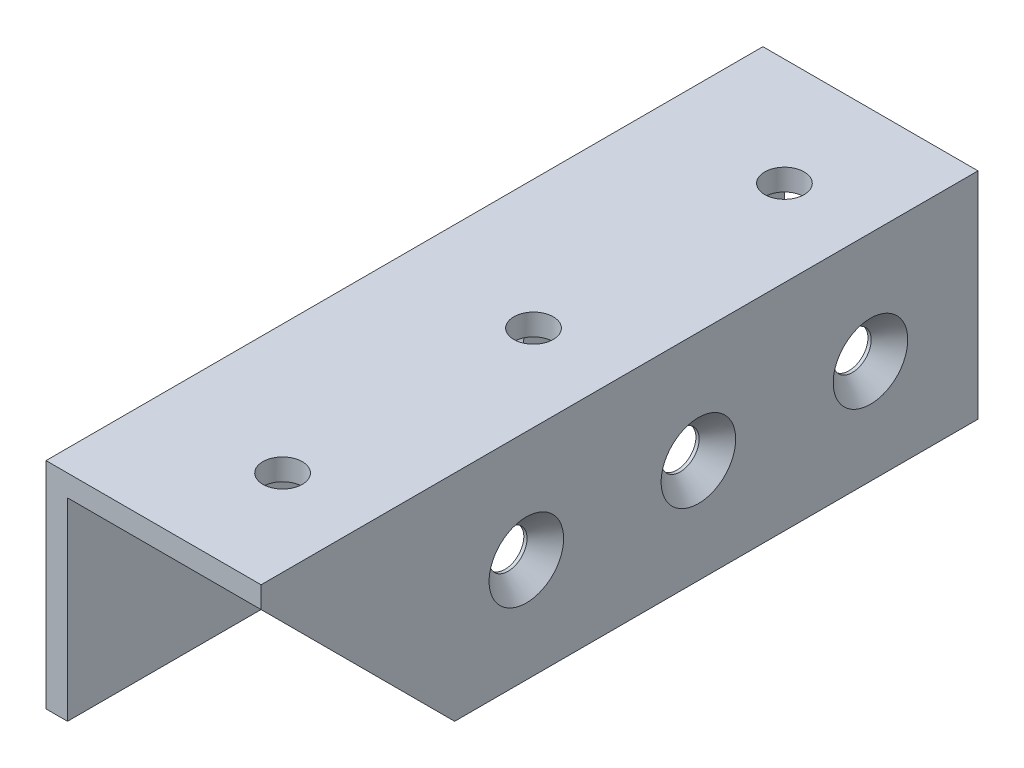
SolidWorks part; units mm, degrees
material "1060 Alloy"
ref_plane "Płaszczyzna przednia" through (0, 0, 0) normal (0, 0, 1) x (1, 0, 0)
ref_plane "Płaszczyzna górna" through (0, 0, 0) normal (0, 1, 0) x (1, 0, 0)
ref_plane "Płaszczyzna prawa" through (0, 0, 0) normal (1, 0, 0) x (0, 0, -1)
sketch "Szkic1" plane through (0, 0, 0) normal (0, 0, 1) x (1, 0, 0)
  line L0 (0, 0) -> (0, 30)
  line L1 (0, 30) -> (30, 30)
  line L2 (30, 30) -> (30, 0)
  line L3 (30, 0) -> (27, 0)
  line L4 (27, 0) -> (27, 27)
  line L5 (27, 27) -> (3, 27)
  line L6 (3, 27) -> (3, 0)
  line L7 (3, 0) -> (0, 0)
  dimension "D1" = 3
  dimension "D2" = 3
  dimension "D3" = 3
  dimension "D4" = 30
  dimension "30" = 30
extrude "Dodanie-wyciągnięcie1" add sketch "Szkic1" along normal blind 100
hole_wizard "M5 Clearance Hole1" positions "Sketch1" profile "Sketch2" hole size "M5" standard "ISO" end condition through all
sketch "Sketch1" plane through (0, 30, 0) normal (0, 1, 0) x (1, 0, 0)
  line L0 (30, -100) -> (0, -100) construction
  line L1 (30, -100) -> (30, 0) construction
  point P0 (18, -50)
  point P2 (18, -15)
  point P4 (18, -85)
  dimension "D1" = 35
  dimension "D2" = 35
  dimension "D3" = 15
  dimension "D4" = 12
sketch "Sketch2" plane through (18, 30, 50) normal (1, 0, 0) x (0, 0, 1)
  line L0 (0, 0) -> (0, 30)
  line L1 (0, 30) -> (2.75, 30)
  line L2 (2.75, 30) -> (2.75, 0)
  line L5 (2.75, 0) -> (0, 0)
  line L11 (0, -6.35) -> (0, 107.95) construction
  dimension "Thru Hole Dia." = 5.5
  dimension "Thru Hole Depth" = 30
hole_wizard "CSK for M5 Countersunk Flat Head Screw1" positions "Sketch3" profile "Sketch4" countersink size "M5" standard "DIN" end condition through all
sketch "Sketch3" plane through (30, 0, 0) normal (1, 0, 0) x (0, 0, -1)
  line L0 (0, 0) -> (0, 30) construction
  line L3 (-100, 27) -> (0, 27) construction
  point P0 (-15, 14.5)
  point P2 (-63, 14.5)
  point P4 (-39, 14.5)
  dimension "D1" = 24
  dimension "D2" = 24
  dimension "D3" = 15
  dimension "D4" = 12.5
sketch "Sketch4" plane through (30, 14.5, 15) normal (0, 1, 0) x (0, 0, -1)
  line L0 (0, 0) -> (0, 30)
  line L1 (0, 30) -> (2.65, 30)
  line L2 (2.65, 30) -> (2.65, 2.55)
  line L3 (2.65, 2.55) -> (5.2, 0)
  line L5 (5.2, 0) -> (0, 0)
  line L6 (-2.65, 2.55) -> (-5.2, 0) construction
  line L11 (0, -6.35) -> (0, 107.95) construction
  dimension "Thru Hole Dia." = 5.3
  dimension "Thru Hole Depth" = 30
  dimension "Near C'Sink Dia." = 10.4
  dimension "Near C'Sink Angle" = 90
chamfer "Chamfer1" distance 27 angle 45 1 edges at (28.5, 0, 100)
